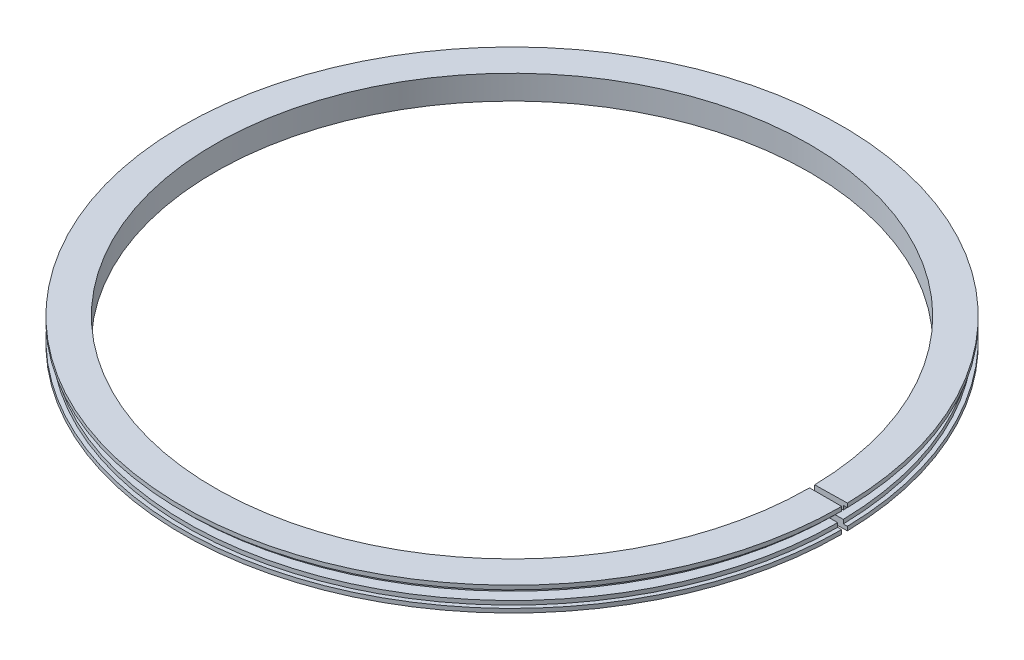
SolidWorks part; units mm, degrees
ref_plane "前视基准面" through (0, 0, 0) normal (0, 0, 1) x (1, 0, 0)
ref_plane "上视基准面" through (0, 0, 0) normal (0, 1, 0) x (1, 0, 0)
ref_plane "右视基准面" through (0, 0, 0) normal (1, 0, 0) x (0, 0, -1)
sketch "草图1" plane through (0, 0, 0) normal (0, 0, 1) x (1, 0, 0)
  line L0 (41, 3) -> (41, 2.5)
  line L1 (40.5, 2.5) -> (40.5, 2)
  line L2 (38.5, 2) -> (38.5, 1)
  line L3 (37, 3) -> (37, 0)
  line L4 (0, 14.4931) -> (0, -8.8647) construction
  line L5 (40.5, 0.5) -> (41, 0.5)
  line L6 (38.5, 1) -> (40.5, 1)
  line L7 (38.5, 2) -> (40.5, 2)
  line L8 (40.5, 2.5) -> (41, 2.5)
  line L9 (37, 3) -> (41, 3)
  line L10 (37, 0) -> (41, 0)
  line L11 (41, 0.5) -> (41, 0)
  line L12 (40.5, 1) -> (40.5, 0.5)
  dimension "D1" = 37
  dimension "D2" = 4
  dimension "D3" = 0.5
  dimension "D4" = 2
  dimension "D5" = 0.5
  dimension "D6" = 0.5
  dimension "D7" = 3
  dimension "D8" = 0.5
  dimension "D9" = 0.5
revolve "旋转1" add sketch "草图1" angle 359 about L4
